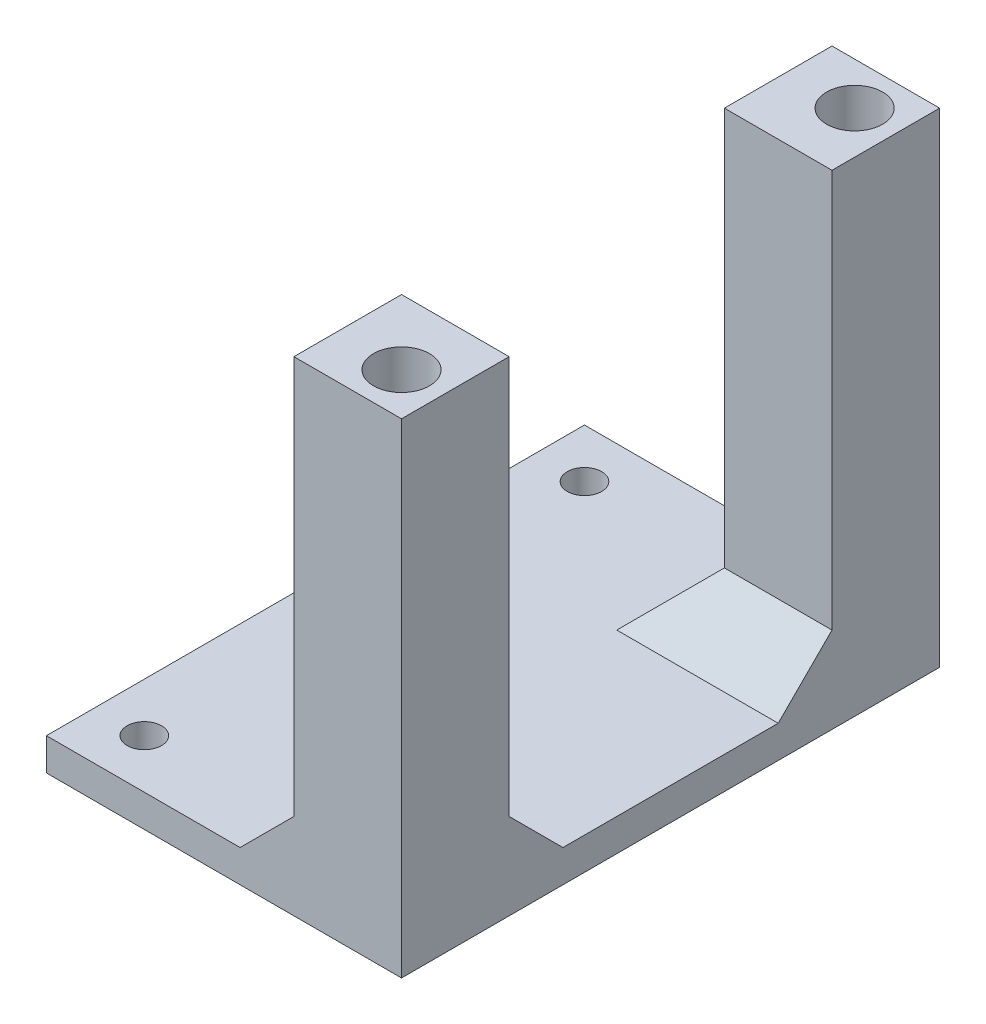
SolidWorks part; units mm, degrees
ref_plane "Front Plane" through (0, 0, 0) normal (0, 0, 1) x (1, 0, 0)
ref_plane "Top Plane" through (0, 0, 0) normal (0, 1, 0) x (1, 0, 0)
ref_plane "Right Plane" through (0, 0, 0) normal (1, 0, 0) x (0, 0, -1)
sketch "Sketch1" plane through (0, 0, 0) normal (0, 1, 0) x (1, 0, 0)
  line L1 (-6.5124, 9.686) -> (1.4876, 9.686)
  line L2 (-6.5124, 9.686) -> (-6.5124, -40.314)
  line L3 (-6.5124, -40.314) -> (1.4876, -40.314)
  line L4 (1.4876, 9.686) -> (1.4876, -40.314)
  line L5 (1.4876, 9.686) -> (26.4876, 9.686)
  line L6 (1.4876, 9.686) -> (1.4876, -40.314)
  line L7 (1.4876, -40.314) -> (26.4876, -40.314)
  line L8 (26.4876, 9.686) -> (26.4876, -40.314)
  circle A0 centre (-1.9624, -35.764) radius 1.6
  circle A1 centre (-1.9624, 5.136) radius 1.6
  dimension "D4" = 3.2
  dimension "D5" = 3.2
  dimension "D6" = 4.55
  dimension "D7" = 4.55
  dimension "D8" = 4.55
  dimension "D9" = 4.55
  dimension "D1" = 8
  dimension "D2" = 50
  dimension "D3" = 25
extrude "Boss-Extrude1" add sketch "Sketch1" along normal blind 3 contours A1 | A0 | L5 L8 L7 L3 L2 L1
sketch "Sketch2" plane through (0, 3, 0) normal (0, 1, 0) x (1, 0, 0)
  line L1 (26.4876, -40.314) -> (16.4876, -40.314)
  line L2 (26.4876, -40.314) -> (26.4876, -30.314)
  line L3 (26.4876, -30.314) -> (16.4876, -30.314)
  line L4 (16.4876, -40.314) -> (16.4876, -30.314)
  line L5 (26.4876, 9.686) -> (16.4876, 9.686)
  line L6 (26.4876, 9.686) -> (26.4876, -0.314)
  line L7 (26.4876, -0.314) -> (16.4876, -0.314)
  line L8 (16.4876, 9.686) -> (16.4876, -0.314)
  dimension "D1" = 10
  dimension "D2" = 10
  dimension "D3" = 10
  dimension "D4" = 10
extrude "Boss-Extrude2" add sketch "Sketch2" along normal blind 42
chamfer "Chamfer1" distance 5 angle 45 4 edges at (16.4876, 3, -4.686) (21.4876, 3, 0.314) (16.4876, 3, 35.314) (21.4876, 3, 30.314)
ref_plane "Plane1" through (0, 45, 0) normal (0, 1, 0) x (1, 0, 0)
sketch "Sketch3" plane through (0, 45, 0) normal (0, 1, 0) x (1, 0, 0)
  line L0 (26.4876, -40.314) -> (26.4876, -30.314) construction
  line L1 (16.4876, -40.314) -> (26.4876, -40.314) construction
  line L2 (26.4876, -0.314) -> (26.4876, 9.686) construction
  line L3 (26.4876, 9.686) -> (16.4876, 9.686) construction
  circle A0 centre (22.5376, -36.364) radius 2.6
  circle A1 centre (22.5376, 5.736) radius 2.6
  dimension "D1" = 5.2
  dimension "D3" = 3.95
  dimension "D4" = 5.2
  dimension "D6" = 3.95
  dimension "D2" = 3.95
  dimension "D5" = 3.95
extrude "Cut-Extrude1" cut sketch "Sketch3" against normal blind 52
